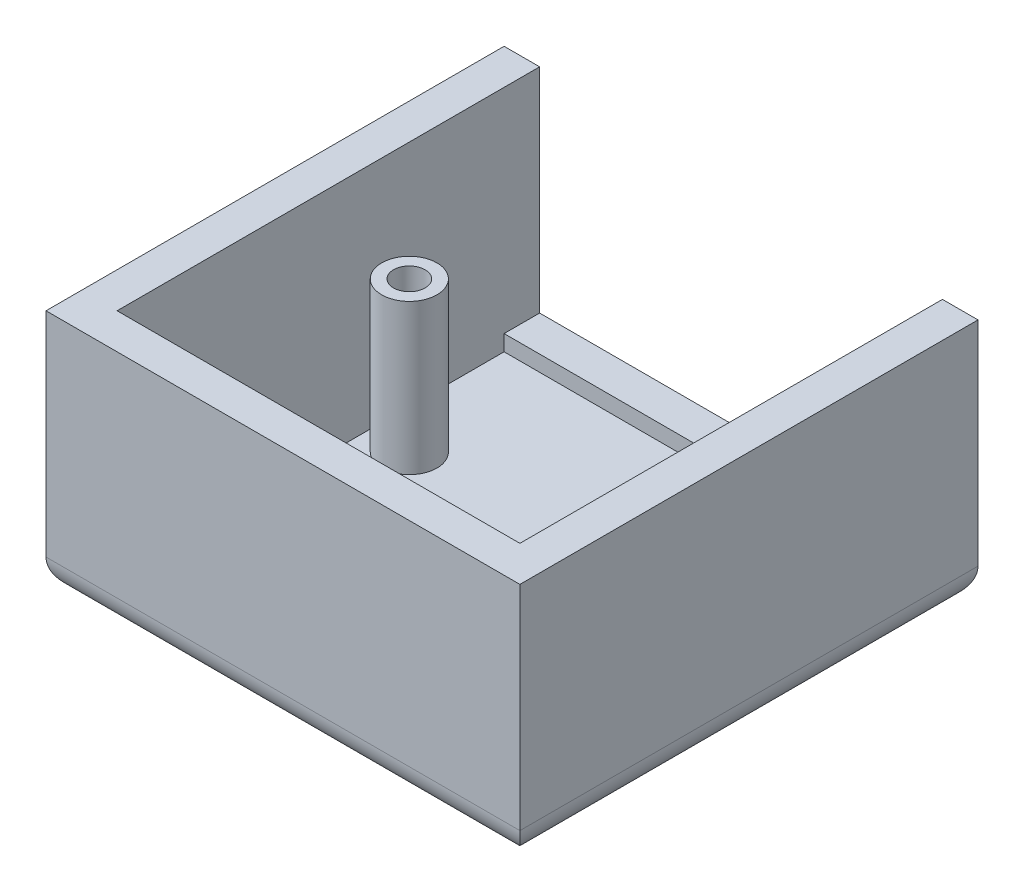
SolidWorks part; units mm, degrees
ref_plane "Alzado" through (0, 0, 0) normal (0, 0, 1) x (1, 0, 0)
ref_plane "Planta" through (0, 0, 0) normal (0, 1, 0) x (1, 0, 0)
ref_plane "Vista lateral" through (0, 0, 0) normal (1, 0, 0) x (0, 0, -1)
sketch "Croquis1" plane through (0, 0, 0) normal (0, 1, 0) x (1, 0, 0)
  line L1 (15, 14.5) -> (-15, 14.5)
  line L2 (15, 14.5) -> (15, -14.5)
  line L3 (15, -14.5) -> (-15, -14.5)
  line L4 (-15, 14.5) -> (-15, -14.5)
  line L5 (15, 14.5) -> (-15, -14.5) construction
  line L6 (15, -14.5) -> (-15, 14.5) construction
  point P0 (0, 0)
  dimension "D1" = 30
  dimension "D2" = 29
extrude "Saliente-Extruir1" add sketch "Croquis1" along normal blind 15.5
sketch "Croquis2" plane through (0, 15.5, 0) normal (0, 1, 0) x (1, 0, 0)
  line L1 (-12.75, -12.25) -> (12.75, -12.25)
  line L2 (-12.75, -12.25) -> (-12.75, 12.25)
  line L3 (-12.75, 12.25) -> (12.75, 12.25)
  line L4 (12.75, -12.25) -> (12.75, 12.25)
  line L5 (-12.75, -12.25) -> (12.75, 12.25) construction
  line L6 (-12.75, 12.25) -> (12.75, -12.25) construction
  point P0 (0, 0)
  dimension "D1" = 25.5
  dimension "D2" = 24.5
extrude "Cortar-Extruir1" cut sketch "Croquis2" against normal blind 14.5
fillet "Redondeo1" radius 2 4 edges at (0, 0, -14.5) (15, 0, 0) (-15, 0, 0) (0, 0, 14.5)
sketch "Croquis6" plane through (0, 0, -14.5) normal (0, 0, -1) x (-1, 0, 0)
  line L0 (-15, 15.5) -> (15, 15.5) construction
  line L1 (-12.75, 15.5) -> (12.75, 15.5)
  line L2 (-12.75, 15.5) -> (-12.75, 2)
  line L3 (-12.75, 2) -> (12.75, 2)
  line L4 (12.75, 15.5) -> (12.75, 2)
  line L5 (-15, 2) -> (15, 2) construction
  line L6 (-15, 15.5) -> (-15, 2) construction
  line L7 (15, 15.5) -> (15, 2) construction
  dimension "D1" = 2.25
  dimension "D2" = 2.25
sketch "Croquis5" plane through (0, 1, 0) normal (0, 1, 0) x (1, 0, 0)
  circle A0 centre (0, -3.9077) radius 6
  dimension "D1" = 12
extrude "Cortar-Extruir3" cut sketch "Croquis5" against normal blind 5
extrude "Cortar-Extruir5" cut sketch "Croquis6" along normal blind 0.75 and the other way blind 3
sketch "Croquis3" plane through (0, 1, 0) normal (0, 1, 0) x (1, 0, 0)
  line L0 (0, -15.1489) -> (0, 15.1489) construction
  line L2 (-12.75, -12.25) -> (12.75, -12.25) construction
  line L3 (12.75, -12.25) -> (12.75, 12.25) construction
  circle A0 centre (10.25, -9.75) radius 1
  circle A1 centre (10.25, 3.75) radius 1
  circle A2 centre (10.25, -9.75) radius 1.75
  circle A3 centre (10.25, 3.75) radius 1.75
  circle A4 centre (-10.25, 3.75) radius 1.75
  circle A5 centre (-10.25, -9.75) radius 1.75
  circle A6 centre (-10.25, 3.75) radius 1
  circle A7 centre (-10.25, -9.75) radius 1
  point P4 (0, 0)
  dimension "D1" = 2
  dimension "D5" = 3.5
  dimension "D2" = 13.5
  dimension "D3" = 2.5
  dimension "D4" = 2.5
extrude "Saliente-Extruir2" add sketch "Croquis3" along normal blind 9.5
